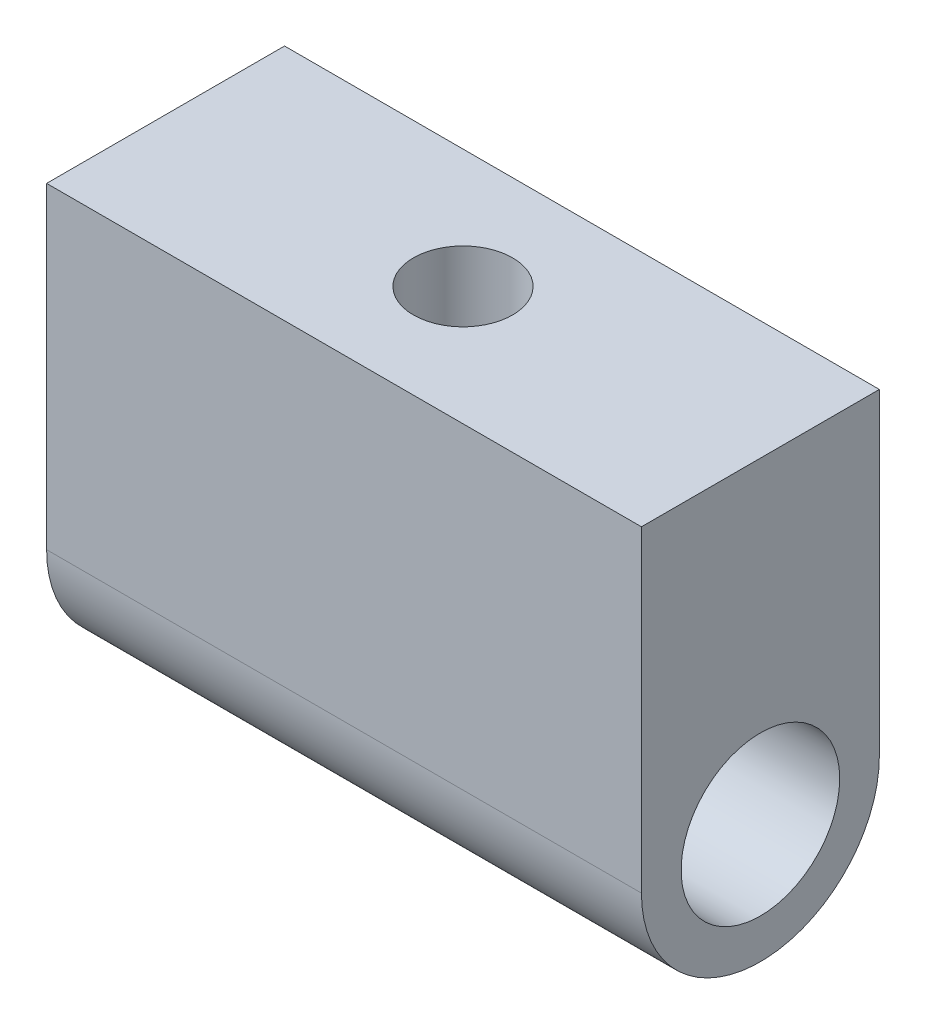
SolidWorks part; units mm, degrees
ref_plane "Front Plane" through (0, 0, 0) normal (0, 0, 1) x (1, 0, 0)
ref_plane "Top Plane" through (0, 0, 0) normal (0, 1, 0) x (1, 0, 0)
ref_plane "Right Plane" through (0, 0, 0) normal (1, 0, 0) x (0, 0, -1)
sketch "Sketch1" plane through (0, 0, 0) normal (1, 0, 0) x (0, 0, -1)
  line L1 (-6, 8) -> (6, 8)
  line L2 (-6, 8) -> (-6, -8)
  line L4 (6, 8) -> (6, -8)
  line L5 (-6, 8) -> (1.68, -2.24) construction
  line L6 (-1.68, -2.24) -> (6, 8) construction
  arc A0 (-6, -8) -> (6, -8) centre (0, -8) ccw
  circle A1 centre (0, -8) radius 4
  point P0 (0, 0)
  dimension "D3" = 12
  dimension "D4" = 8
  dimension "D1" = 16
  dimension "D2" = 12
extrude "Boss-Extrude1" add sketch "Sketch1" along normal blind 30
sketch "Sketch2" plane through (0, 8, 0) normal (0, 1, 0) x (1, 0, 0)
  line L0 (30, -6) -> (0, -6) construction
  line L1 (30, 6) -> (30, -6) construction
  circle A0 centre (15, 0) radius 2.5
  point P2 (0, 0)
  point P5 (15, -6)
  point P8 (30, 0)
  dimension "D1" = 5
  dimension "D2" = 6
  dimension "D3" = 15
extrude "Cut-Extrude1" cut sketch "Sketch2" against normal blind 5
